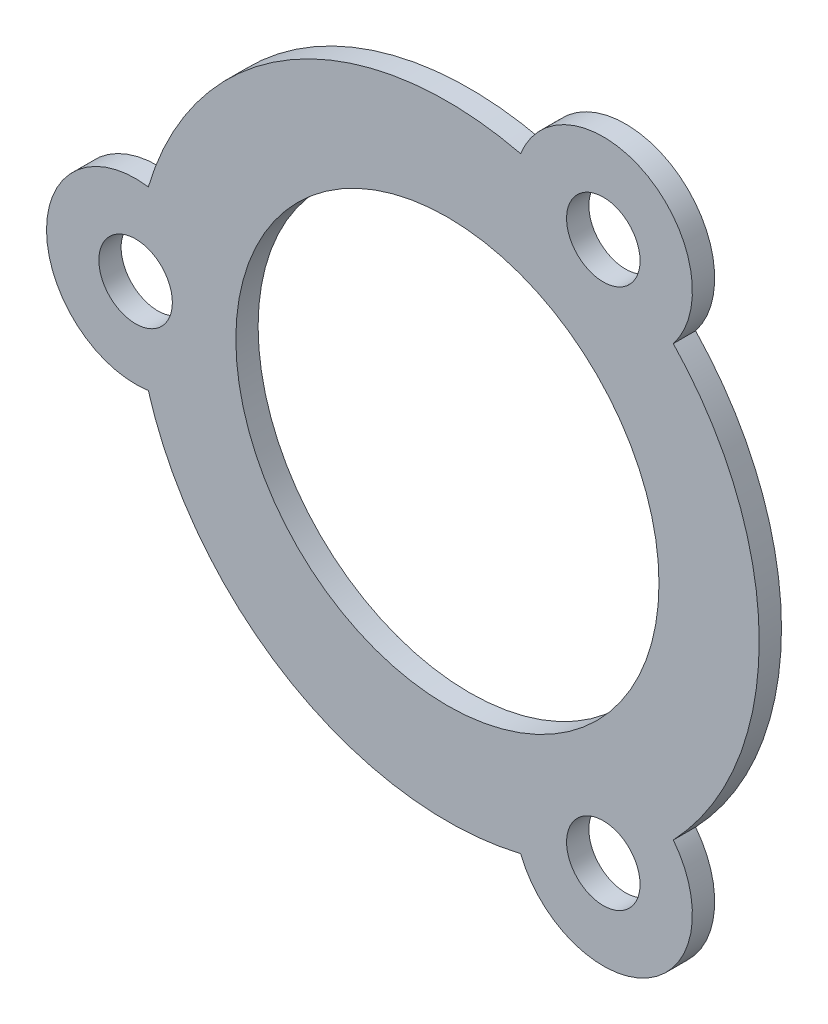
SolidWorks part; units mm, degrees
ref_plane "Front Plane" through (0, 0, 0) normal (0, 0, 1) x (1, 0, 0)
ref_plane "Top Plane" through (0, 0, 0) normal (0, 1, 0) x (1, 0, 0)
ref_plane "Right Plane" through (0, 0, 0) normal (1, 0, 0) x (0, 0, -1)
sketch "Sketch1" plane through (0, 0, 0) normal (0, 0, 1) x (1, 0, 0)
  arc A0 (10.1429, 9.65) -> (3.2857, 13.609) centre (7, 12.1244) ccw construction
  arc A1 (10.1429, -9.65) -> (10.1429, 9.65) centre (0, 0) ccw construction
  arc A2 (3.2857, -13.609) -> (10.1429, -9.65) centre (7, -12.1244) ccw construction
  arc A3 (-13.4286, -3.959) -> (3.2857, -13.609) centre (0, 0) ccw construction
  arc A4 (-13.4286, 3.959) -> (-13.4286, -3.959) centre (-14, 0) ccw construction
  arc A5 (3.2857, 13.609) -> (-13.4286, 3.959) centre (0, 0) ccw construction
  arc A6 (10.1429, 9.65) -> (3.2857, 13.609) centre (7, 12.1244) ccw
  arc A7 (10.1429, -9.65) -> (10.1429, 9.65) centre (0, 0) ccw
  arc A8 (3.2857, -13.609) -> (10.1429, -9.65) centre (7, -12.1244) ccw
  arc A9 (-13.4286, -3.959) -> (3.2857, -13.609) centre (0, 0) ccw
  arc A10 (-13.4286, 3.959) -> (-13.4286, -3.959) centre (-14, 0) ccw
  arc A11 (3.2857, 13.609) -> (-13.4286, 3.959) centre (0, 0) ccw
  circle A14 centre (7, 12.1244) radius 1.65
  circle A15 centre (7, -12.1244) radius 1.65
  circle A16 centre (-14, 0) radius 1.65
  circle A18 centre (0, 0) radius 9.5
  circle A19 centre (0, 0) radius 9.5
  dimension "D1" = 3.3
  dimension "D2" = 0
extrude "Boss-Extrude1" add sketch "Sketch1" along normal blind 1
